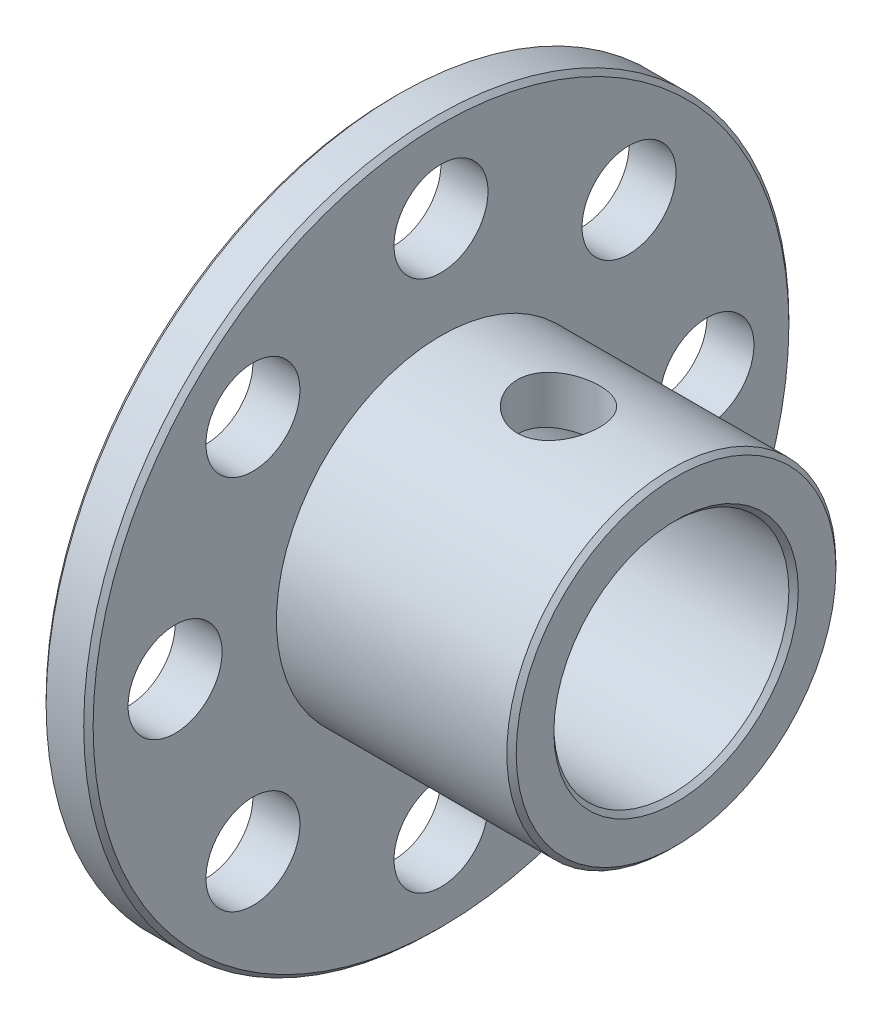
SolidWorks part; units mm, degrees
ref_plane "前视基准面" through (0, 0, 0) normal (0, 0, 1) x (1, 0, 0)
ref_plane "上视基准面" through (0, 0, 0) normal (0, 1, 0) x (1, 0, 0)
ref_plane "右视基准面" through (0, 0, 0) normal (1, 0, 0) x (0, 0, -1)
sketch "草图1" plane through (0, 0, 0) normal (1, 0, 0) x (0, 0, -1)
  circle A0 centre (0, 0) radius 15
  dimension "D1" = 30
extrude "凸台-拉伸1" add sketch "草图1" along normal blind 2
sketch "草图2" plane through (2, 0, 0) normal (1, 0, 0) x (0, 0, -1)
  circle A0 centre (0, 0) radius 7
  dimension "D1" = 14
extrude "凸台-拉伸2" add sketch "草图2" along normal blind 10
sketch "草图3" plane through (2, 0, 0) normal (1, 0, 0) x (0, 0, -1)
  line L0 (0, 0) -> (0, 30.8145) construction
  circle A13 centre (0, 11.3137) radius 2
  circle A14 centre (8, 8) radius 2
  circle A15 centre (11.3137, 0) radius 2
  circle A16 centre (8, -8) radius 2
  circle A17 centre (0, -11.3137) radius 2
  circle A18 centre (-8, -8) radius 2
  circle A19 centre (-11.3137, 0) radius 2
  circle A20 centre (-8, 8) radius 2
  point P21 (0, 0)
  point P47 (0, 0)
  dimension "D1" = 4
  dimension "D2" = 11.3137
  dimension "D3" = 8
  dimension "D4" = 16
extrude "切除-拉伸1" cut sketch "草图3" against normal through all
sketch "草图4" plane through (12, 0, 0) normal (1, 0, 0) x (0, 0, -1)
  circle A0 centre (0, 0) radius 5
  dimension "D1" = 10
extrude "切除-拉伸2" cut sketch "草图4" against normal through all
chamfer "倒角1" distance 0.2 angle 45 5 edges at (0, 0, -5) (2, 0, -15) (0, 0, -15) (12, 0, -5) (12, 0, -7)
sketch "草图5" plane through (0, 0, 0) normal (0, 1, 0) x (1, 0, 0)
  line L0 (0, 0) -> (7, 0) construction
  circle A0 centre (7, 0) radius 1.75
  dimension "D2" = 3.5
  dimension "D1" = 7
extrude "切除-拉伸3" cut sketch "草图5" along normal blind 10
cosmetic thread "装饰螺纹线1" parameters "D2"=4
